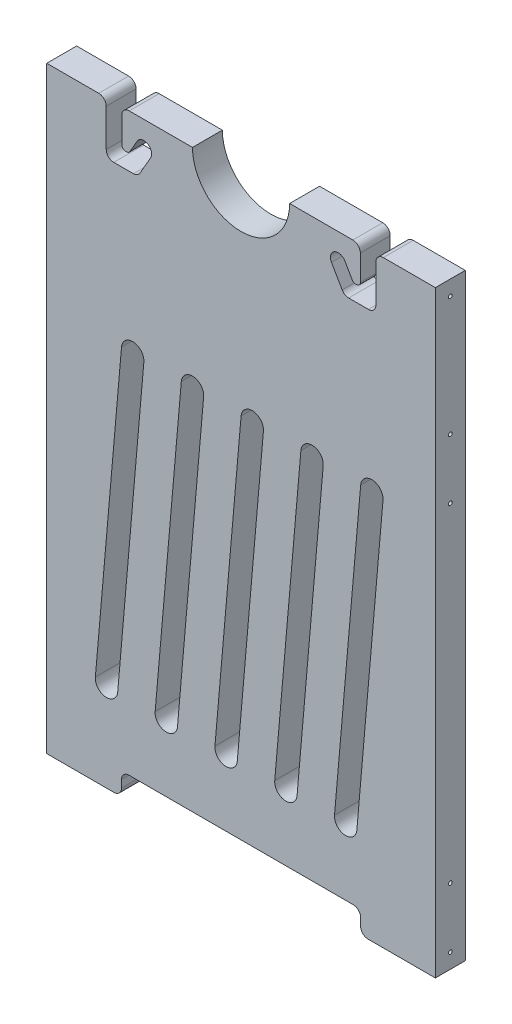
SolidWorks part; units mm, degrees
material "Delrin 2700 NC010, Low Viscosity Acetal Copolymer (SS)"
ref_plane "Front Plane" through (0, 0, 0) normal (0, 0, 1) x (1, 0, 0)
ref_plane "Top Plane" through (0, 0, 0) normal (0, 1, 0) x (1, 0, 0)
ref_plane "Right Plane" through (0, 0, 0) normal (1, 0, 0) x (0, 0, -1)
sketch "Sketch1" plane through (0, 0, 0) normal (0, 1, 0) x (1, 0, 0)
  line L1 (-82.55, -6.35) -> (82.55, -6.35)
  line L2 (-82.55, -6.35) -> (-82.55, 6.35)
  line L3 (-82.55, 6.35) -> (82.55, 6.35)
  line L4 (82.55, -6.35) -> (82.55, 6.35)
  line L5 (-82.55, -6.35) -> (82.55, 6.35) construction
  line L6 (-82.55, 6.35) -> (82.55, -6.35) construction
  point P0 (0, 0)
  dimension "D1" = 165.1
  dimension "D2" = 12.7
extrude "Boss-Extrude1" add sketch "Sketch1" along normal mid plane 254
sketch "Sketch2" plane through (0, 0, 6.35) normal (0, 0, 1) x (1, 0, 0)
  line L0 (-82.55, 127) -> (82.55, 127) construction
  circle A0 centre (0, 127) radius 20.6375
  dimension "D1" = 41.275
extrude "Cut-Extrude1" cut sketch "Sketch2" against normal through all
sketch "Sketch4" plane through (0, 0, 6.35) normal (0, 0, 1) x (1, 0, 0)
  line L0 (57.277, 127) -> (57.277, 104.775)
  line L1 (20.6375, 127) -> (82.55, 127) construction
  line L2 (57.277, 104.775) -> (43.878, 104.775)
  line L3 (43.878, 104.775) -> (38.4154, 114.2365)
  line L5 (44.1346, 117.5385) -> (47.6908, 111.379)
  line L6 (47.6908, 111.379) -> (50.673, 111.379)
  line L7 (50.673, 111.379) -> (50.673, 127)
  line L8 (50.673, 127) -> (57.277, 127)
  line L9 (82.55, 127) -> (82.55, -127) construction
  line L10 (0, 0) -> (0, 185.1482) construction
  line L11 (-50.673, 127) -> (-57.277, 127)
  line L12 (-50.673, 111.379) -> (-50.673, 127)
  line L13 (-47.6908, 111.379) -> (-50.673, 111.379)
  line L14 (-44.1346, 117.5385) -> (-47.6908, 111.379)
  line L15 (-43.878, 104.775) -> (-38.4154, 114.2365)
  line L16 (-57.277, 104.775) -> (-43.878, 104.775)
  line L17 (-57.277, 127) -> (-57.277, 104.775)
  arc A0 (44.1346, 117.5385) -> (38.4154, 114.2365) centre (41.275, 115.8875) ccw
  arc A1 (-44.1346, 117.5385) -> (-38.4154, 114.2365) centre (-41.275, 115.8875) cw
  point P6 (53.975, 127)
  point P13 (41.1467, 109.5058)
  dimension "D8" = 3.302
  dimension "D1" = 6.604
  dimension "D2" = 28.575
  dimension "D3" = 22.225
  dimension "D4" = 120
  dimension "D5" = 6.604
  dimension "D6" = 6.604
  dimension "D7" = 12.7
  dimension "D9" = 11.1125
extrude "Cut-Extrude3" cut sketch "Sketch4" against normal through all
fillet "Fillet1" radius 3.175 8 edges at (-57.277, 104.775, 0) (-43.878, 104.775, 0) (-57.277, 127, 0) (-50.673, 127, 0) (50.673, 127, 0) (57.277, 127, 0) (57.277, 104.775, 0) (43.878, 104.775, 0)
fillet "Fillet2" radius 1.5875 4 edges at (-50.673, 111.379, 0) (-47.6908, 111.379, 0) (47.6908, 111.379, 0) (50.673, 111.379, 0)
sketch "Sketch5" plane through (0, 0, 6.35) normal (0, 0, 1) x (1, 0, 0)
  line L0 (-82.55, -127) -> (82.55, -127) construction
  line L1 (-50.8, -127) -> (50.8, -127)
  line L2 (-50.8, -127) -> (-50.8, -117.475)
  line L3 (-50.8, -117.475) -> (50.8, -117.475)
  line L4 (50.8, -127) -> (50.8, -117.475)
  point P6 (0, -127)
  point P7 (0, -127)
  dimension "D1" = 9.525
  dimension "D2" = 101.6
extrude "Cut-Extrude4" cut sketch "Sketch5" against normal through all
fillet "Fillet3" radius 3.175 4 edges at (50.8, -127, 0) (50.8, -117.475, 0) (-50.8, -117.475, 0) (-50.8, -127, 0)
hole_wizard "1/16 (0.0625) Diameter Hole1" positions "Sketch6" profile "Sketch7" hole size "1/16" standard "ANSI Inch"
sketch "Sketch6" plane through (82.55, 0, 0) normal (1, 0, 0) x (0, 0, -1)
  line L0 (-6.35, -127) -> (6.35, -127) construction
  point P0 (0, -120.65)
  point P2 (0, -95.25)
  point P4 (0, 44.45)
  point P6 (0, 69.85)
  point P8 (0, 120.65)
  point P13 (0, -127)
  dimension "D1" = 0
other "AlignGroup1" parameters "D1"=0, "D2"=6.35, "D3"=31.75, "D4"=171.45, "D5"=196.85, "D6"=247.65
sketch "Sketch7" plane through (82.55, -120.65, 0) normal (0, 1, 0) x (0, 0, -1)
  line L0 (0, 0) -> (0, 16.3519)
  line L1 (0, 16.3519) -> (0.7937, 15.875)
  line L2 (0.7937, 15.875) -> (0.7937, 0)
  line L5 (0.7937, 0) -> (0, 0)
  line L10 (0, 16.3519) -> (-0.7938, 15.875) construction
  line L11 (0, -6.35) -> (0, 107.95) construction
  dimension "Hole Dia." = 1.5875
  dimension "Hole Depth" = 15.875
  dimension "Drill Angle" = 118
hole_wizard "1/16 (0.0625) Diameter Hole2" positions "Sketch8" profile "Sketch9" hole size "1/16" standard "ANSI Inch"
sketch "Sketch8" plane through (-82.55, 0, 0) normal (-1, 0, 0) x (0, 0, 1)
  point P0 (0, -120.65)
  point P3 (0, -95.25)
  point P6 (0, 44.45)
  point P9 (0, 69.85)
  point P12 (0, 120.65)
sketch "Sketch9" plane through (-82.55, -120.65, 0) normal (0, 1, 0) x (0, 0, 1)
  line L0 (0, 0) -> (0, 16.3519)
  line L1 (0, 16.3519) -> (0.7937, 15.875)
  line L2 (0.7937, 15.875) -> (0.7937, 0)
  line L5 (0.7937, 0) -> (0, 0)
  line L10 (0, 16.3519) -> (-0.7937, 15.875) construction
  line L11 (0, -6.35) -> (0, 107.95) construction
  dimension "Hole Dia." = 1.5875
  dimension "Hole Depth" = 15.875
  dimension "Drill Angle" = 118
sketch "Sketch10" plane through (0, 0, 6.35) normal (0, 0, 1) x (1, 0, 0)
  line L0 (-57.15, -88.9) -> (-46.0389, 38.1) construction
  line L1 (-61.8944, -88.4849) -> (-50.7833, 38.5151)
  line L2 (-52.4056, -89.3151) -> (-41.2946, 37.6849)
  line L3 (-82.55, -127) -> (-53.975, -127) construction
  line L4 (-82.55, 127) -> (-82.55, -127) construction
  line L5 (-27.0056, -89.3151) -> (-15.8946, 37.6849)
  line L6 (-36.4944, -88.4849) -> (-25.3833, 38.5151)
  line L7 (-31.75, -88.9) -> (-20.6389, 38.1) construction
  line L8 (-1.6056, -89.3151) -> (9.5054, 37.6849)
  line L9 (-11.0944, -88.4849) -> (0.0167, 38.5151)
  line L10 (-6.35, -88.9) -> (4.7611, 38.1) construction
  line L11 (23.7944, -89.3151) -> (34.9054, 37.6849)
  line L12 (14.3056, -88.4849) -> (25.4167, 38.5151)
  line L13 (19.05, -88.9) -> (30.1611, 38.1) construction
  line L14 (49.1944, -89.3151) -> (60.3054, 37.6849)
  line L15 (39.7056, -88.4849) -> (50.8167, 38.5151)
  line L16 (44.45, -88.9) -> (55.5611, 38.1) construction
  line L17 (-52.4056, -89.3151) -> (-27.0056, -89.3151) construction
  arc A0 (-61.8944, -88.4849) -> (-52.4056, -89.3151) centre (-57.15, -88.9) ccw
  arc A1 (-41.2946, 37.6849) -> (-50.7833, 38.5151) centre (-46.0389, 38.1) ccw
  arc A2 (-36.4944, -88.4849) -> (-27.0056, -89.3151) centre (-31.75, -88.9) ccw
  arc A3 (-15.8946, 37.6849) -> (-25.3833, 38.5151) centre (-20.6389, 38.1) ccw
  arc A4 (-11.0944, -88.4849) -> (-1.6056, -89.3151) centre (-6.35, -88.9) ccw
  arc A5 (9.5054, 37.6849) -> (0.0167, 38.5151) centre (4.7611, 38.1) ccw
  arc A6 (14.3056, -88.4849) -> (23.7944, -89.3151) centre (19.05, -88.9) ccw
  arc A7 (34.9054, 37.6849) -> (25.4167, 38.5151) centre (30.1611, 38.1) ccw
  arc A8 (39.7056, -88.4849) -> (49.1944, -89.3151) centre (44.45, -88.9) ccw
  arc A9 (60.3054, 37.6849) -> (50.8167, 38.5151) centre (55.5611, 38.1) ccw
  point P2 (-51.5945, -25.4)
  point P15 (-26.1945, -25.4)
  point P22 (-0.7945, -25.4)
  point P29 (24.6055, -25.4)
  point P36 (50.0055, -25.4)
  dimension "D3" = 4.7625
  dimension "D1" = 38.1
  dimension "D2" = 25.4
  dimension "D4" = 127
  dimension "D5" = 5
  dimension "D7" = 25.4
  dimension "D6" = 5
extrude "Cut-Extrude5" cut sketch "Sketch10" against normal through all
equation "\"D1@Sketch2\"=.8125*2"
equation "\"D8@Sketch4\"=.260/2"
